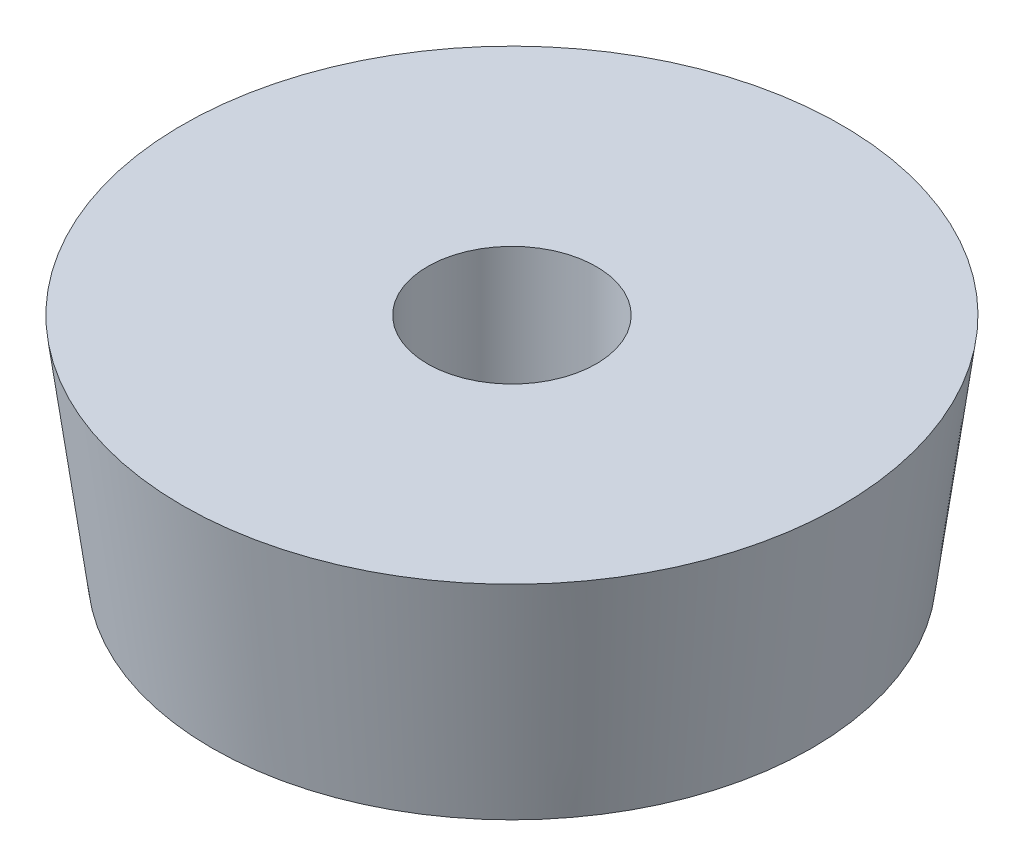
SolidWorks part; units mm, degrees
ref_plane "Front Plane" through (0, 0, 0) normal (0, 0, 1) x (1, 0, 0)
ref_plane "Top Plane" through (0, 0, 0) normal (0, 1, 0) x (1, 0, 0)
ref_plane "Right Plane" through (0, 0, 0) normal (1, 0, 0) x (0, 0, -1)
sketch "Sketch2" plane through (0, 0, 0) normal (0, 1, 0) x (1, 0, 0)
  circle A0 centre (0, 0) radius 50.8
  dimension "D1" = 101.6
extrude "Boss-Extrude3" add sketch "Sketch2" along normal blind 38.1 draft 7.5 draft outward yes
sketch "Sketch3" plane through (0, 38.1, 0) normal (0, 1, 0) x (1, 0, 0)
  circle A0 centre (0, 0) radius 14.2875
  dimension "D1" = 28.575
extrude "Cut-Extrude1" cut sketch "Sketch3" against normal through all
